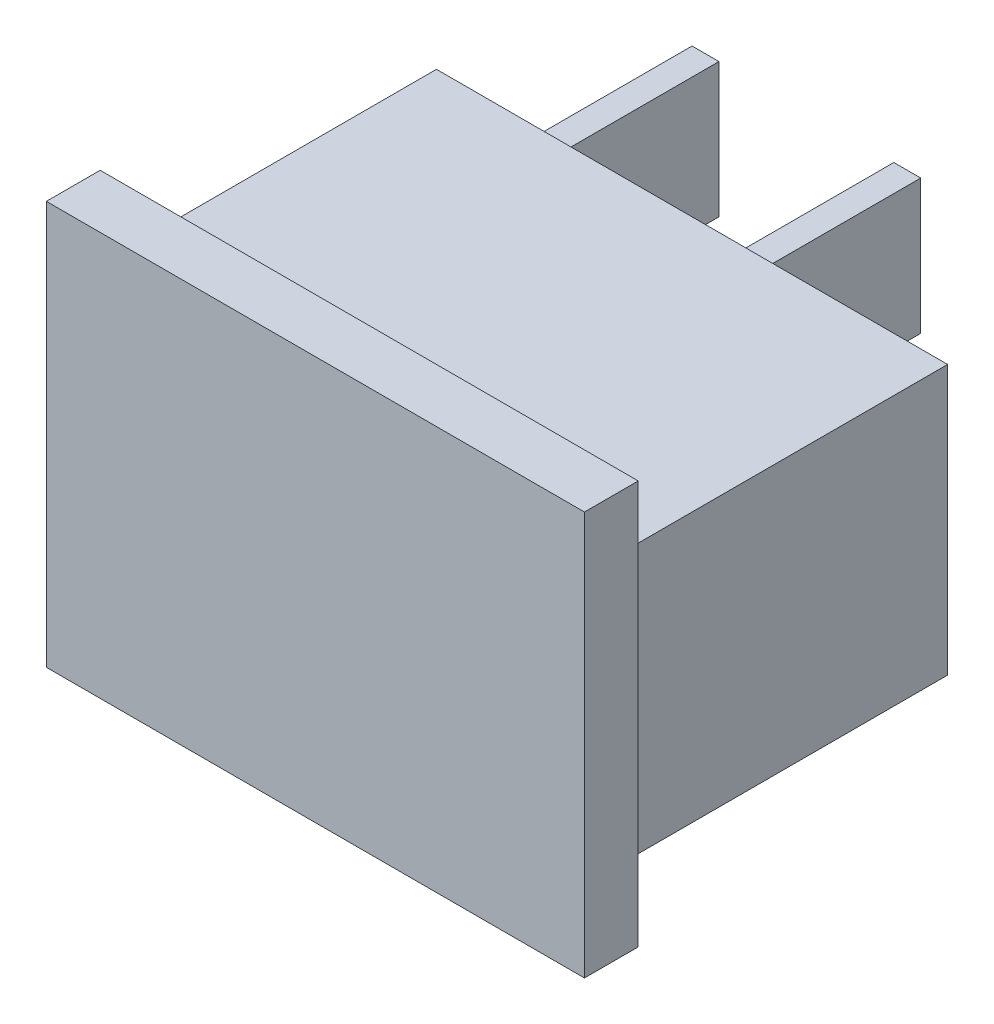
SolidWorks part; units mm, degrees
ref_plane "Plan de face" through (0, 0, 0) normal (0, 0, 1) x (1, 0, 0)
ref_plane "Plan de dessus" through (0, 0, 0) normal (0, 1, 0) x (1, 0, 0)
ref_plane "Plan de droite" through (0, 0, 0) normal (1, 0, 0) x (0, 0, -1)
sketch "Esquisse1" plane through (0, 0, 0) normal (0, 1, 0) x (1, 0, 0)
  line L1 (0, 0) -> (19, 0)
  line L2 (0, 0) -> (0, 12)
  line L3 (0, 12) -> (19, 12)
  line L4 (19, 0) -> (19, 12)
  dimension "D1" = 19
  dimension "D2" = 12
extrude "Boss.-Extru.1" add sketch "Esquisse1" along normal blind 10
sketch "Esquisse2" plane through (0, 0, 0) normal (0, 0, 1) x (1, 0, 0)
  line L0 (0, 5) -> (19, 5) construction
  line L1 (0, 10) -> (0, 0) construction
  line L2 (19, 10) -> (19, 0) construction
  line L4 (19.5, -2.5) -> (-0.5, -2.5)
  line L5 (19.5, -2.5) -> (19.5, 12.5)
  line L6 (19.5, 12.5) -> (-0.5, 12.5)
  line L7 (-0.5, -2.5) -> (-0.5, 12.5)
  line L8 (19.5, -2.5) -> (-0.5, 12.5) construction
  line L9 (19.5, 12.5) -> (-0.5, -2.5) construction
  point P6 (9.5, 5)
  dimension "D1" = 20
  dimension "D2" = 15
extrude "Boss.-Extru.2" add sketch "Esquisse2" along normal blind 2
sketch "Esquisse3" plane through (0, 0, -12) normal (0, 0, -1) x (-1, 0, 0)
  line L0 (-19, 5) -> (0, 5) construction
  line L1 (-19, 10) -> (-19, 0) construction
  line L2 (0, 10) -> (0, 0) construction
  line L4 (-10, 2.5) -> (-9, 2.5)
  line L5 (-10, 2.5) -> (-10, 7.5)
  line L6 (-10, 7.5) -> (-9, 7.5)
  line L7 (-9, 2.5) -> (-9, 7.5)
  line L8 (-10, 2.5) -> (-9, 7.5) construction
  line L9 (-10, 7.5) -> (-9, 2.5) construction
  line L10 (-2.5, 2.5) -> (-1.5, 2.5)
  line L11 (-2.5, 2.5) -> (-2.5, 7.5)
  line L12 (-2.5, 7.5) -> (-1.5, 7.5)
  line L13 (-1.5, 2.5) -> (-1.5, 7.5)
  line L14 (-2.5, 2.5) -> (-1.5, 7.5) construction
  line L15 (-2.5, 7.5) -> (-1.5, 2.5) construction
  point P6 (-9.5, 5)
  point P11 (-2, 5)
  dimension "D1" = 1
  dimension "D2" = 5
  dimension "D3" = 1.5
extrude "Boss.-Extru.3" add sketch "Esquisse3" along normal blind 8
